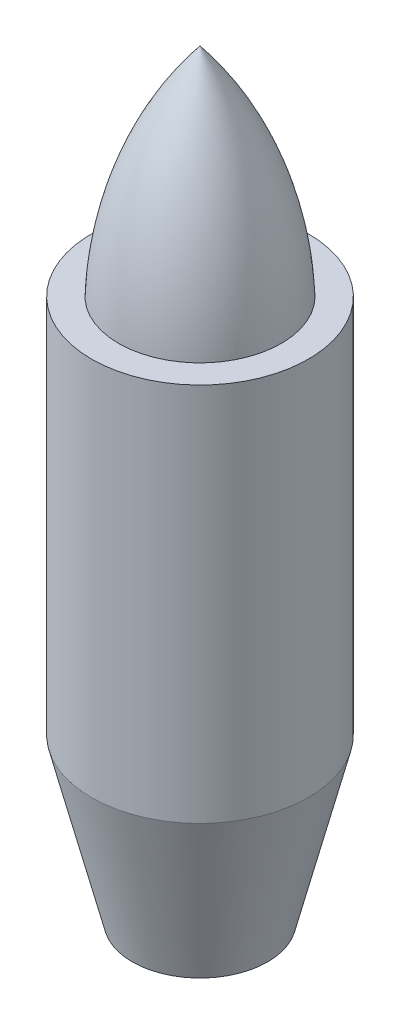
SolidWorks part; units mm, degrees
ref_plane "Front Plane" through (0, 0, 0) normal (0, 0, 1) x (1, 0, 0)
ref_plane "Top Plane" through (0, 0, 0) normal (0, 1, 0) x (1, 0, 0)
ref_plane "Right Plane" through (0, 0, 0) normal (1, 0, 0) x (0, 0, -1)
sketch "Sketch1" plane through (0, 0, 0) normal (0, 1, 0) x (1, 0, 0)
  circle A0 centre (0, 0) radius 200
  dimension "D1" = 400
extrude "Boss-Extrude1" add sketch "Sketch1" along normal blind 700
ref_plane "Plane1" through (0, -300, 0) normal (0, -1, 0) x (-1, 0, 0)
sketch "Sketch2" plane through (0, -300, 0) normal (0, -1, 0) x (-1, 0, 0)
  circle A0 centre (0, 0) radius 125
  dimension "D1" = 250
loft "Loft1" add profiles "Sketch2" section "Sketch2" section edge at (0, 0, 200)
sketch "Sketch3" plane through (0, 0, 0) normal (1, 0, 0) x (0, 0, -1)
  line L0 (0, 1100) -> (0, 700)
  line L1 (200, 700) -> (-200, 700) construction
  arc A0 (-150, 700) -> (0, 1100) centre (527.784, 673.956) cw
  dimension "D1" = 400
revolve "Revolve-Thin1" add sketch "Sketch3" angle 360 about L0
